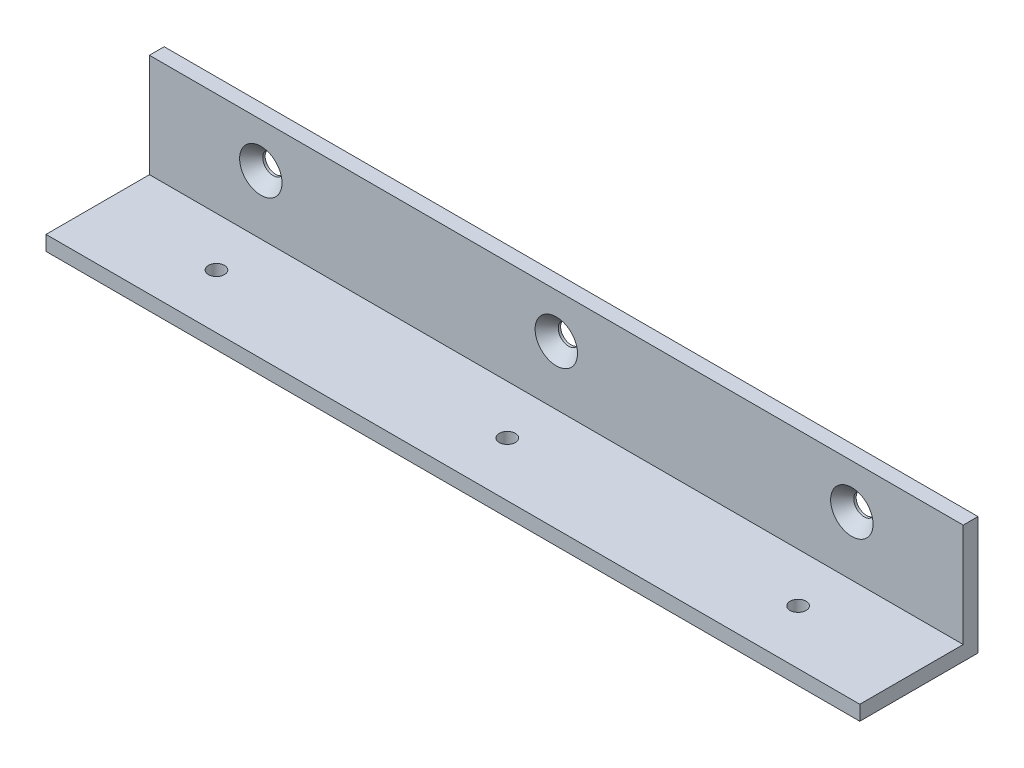
SolidWorks part; units mm, degrees
material "6061-T6 (SS)"
ref_plane "Front Plane" through (0, 0, 0) normal (0, 0, 1) x (1, 0, 0)
ref_plane "Top Plane" through (0, 0, 0) normal (0, 1, 0) x (1, 0, 0)
ref_plane "Right Plane" through (0, 0, 0) normal (1, 0, 0) x (0, 0, -1)
sketch "Sketch1" plane through (0, 0, 0) normal (0, 1, 0) x (1, 0, 0)
  line L1 (-87.4395, -12.7) -> (87.4395, -12.7)
  line L2 (-87.4395, -12.7) -> (-87.4395, 12.7)
  line L3 (-87.4395, 12.7) -> (87.4395, 12.7)
  line L4 (87.4395, -12.7) -> (87.4395, 12.7)
  line L5 (-87.4395, -12.7) -> (87.4395, 12.7) construction
  line L6 (-87.4395, 12.7) -> (87.4395, -12.7) construction
  point P0 (0, 0)
  dimension "D1" = 174.879
  dimension "D2" = 25.4
extrude "Boss-Extrude1" add sketch "Sketch1" along normal blind 3.175
sketch "Sketch2" plane through (0, 3.175, 0) normal (0, 1, 0) x (1, 0, 0)
  line L0 (87.4395, -12.7) -> (87.4395, 12.7) construction
  line L1 (-87.4395, 12.7) -> (87.4395, 12.7)
  line L2 (-87.4395, 12.7) -> (-87.4395, 9.525)
  line L3 (-87.4395, 9.525) -> (87.4395, 9.525)
  line L4 (87.4395, 12.7) -> (87.4395, 9.525)
  dimension "D1" = 3.175
extrude "Boss-Extrude2" add sketch "Sketch2" along normal blind 22.225
hole_wizard "#8-32 Tapped Hole1" positions "Sketch5" profile "Sketch4" tap size "#8-32" standard "Ansi Inch"
sketch "Sketch5" plane through (0, 3.175, 0) normal (0, 1, 0) x (-1, 0, 0)
  line L0 (87.4395, 1.016) -> (-87.4395, 1.016) construction
  line L1 (87.4395, -9.525) -> (87.4395, 12.7) construction
  line L2 (-87.4395, 12.7) -> (-87.4395, -9.525) construction
  line L4 (87.4395, 12.7) -> (-87.4395, 12.7) construction
  point P0 (62.5, 1.016)
  point P1 (0, 1.016)
  point P3 (-62.5, 1.016)
  dimension "D1" = 62.5
  dimension "D2" = 62.5
  dimension "D3" = 11.684
sketch "Sketch4" plane through (-62.5, 3.175, 1.016) normal (1, 0, 0) x (0, 0, 1)
  line L0 (0, 0) -> (0, 11.7058)
  line L1 (0, 11.7058) -> (1.7272, 10.668)
  line L2 (1.7272, 10.668) -> (1.7272, 0)
  line L5 (1.7272, 0) -> (0, 0)
  line L10 (0, 11.7058) -> (-1.7272, 10.668) construction
  line L11 (0, -6.35) -> (0, 107.95) construction
  dimension "Tap Drill Dia." = 3.4544
  dimension "Tap Drill Depth" = 10.668
  dimension "Drill Angle" = 118
hole_wizard "CSK for #8 Flat Head Socket Cap Screw1" positions "Sketch7" profile "Sketch6" countersink size "#8" standard "Ansi Inch" end condition through all
sketch "Sketch7" plane through (0, 0, -9.525) normal (0, 0, 1) x (1, 0, 0)
  line L0 (-87.4395, 25.4) -> (87.4395, 25.4) construction
  point P0 (-63.5, 15.875)
  point P1 (0, 15.875)
  point P3 (63.5, 15.875)
  dimension "D1" = 9.525
  dimension "D2" = 9.525
  dimension "D3" = 9.525
  dimension "D4" = 63.5
  dimension "D5" = 63.5
sketch "Sketch6" plane through (-63.5, 15.875, -9.525) normal (1, 0, 0) x (0, -1, 0)
  line L0 (0, 0) -> (0, 3.175)
  line L1 (0, 3.175) -> (2.2479, 3.175)
  line L2 (2.2479, 3.175) -> (2.2479, 2.659)
  line L3 (2.2479, 2.659) -> (4.5593, 0)
  line L5 (4.5593, 0) -> (0, 0)
  line L6 (-2.2479, 2.659) -> (-4.5593, 0) construction
  line L11 (0, -6.35) -> (0, 107.95) construction
  dimension "Thru Hole Dia." = 4.4958
  dimension "Thru Hole Depth" = 3.175
  dimension "Near C'Sink Dia." = 9.1186
  dimension "Near C'Sink Angle" = 82
